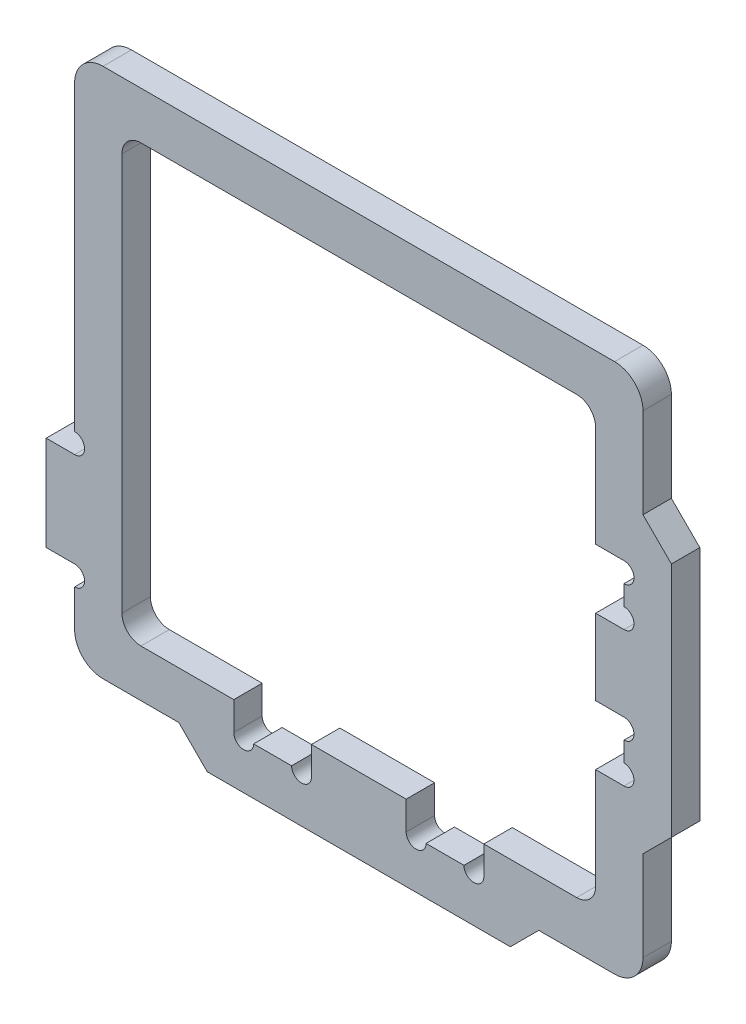
SolidWorks part; units mm, degrees
material "玻纤板"
ref_plane "前视基准面" through (0, 0, 0) normal (0, 0, 1) x (1, 0, 0)
ref_plane "上视基准面" through (0, 0, 0) normal (0, 1, 0) x (1, 0, 0)
ref_plane "右视基准面" through (0, 0, 0) normal (1, 0, 0) x (0, 0, -1)
sketch "草图1" plane through (0, 0, 0) normal (0, 0, 1) x (1, 0, 0)
  line L1 (25, -23) -> (13.2, -23)
  line L2 (25, -23) -> (25, -10.3)
  line L3 (25, 23) -> (-25, 23)
  line L4 (-25, -23) -> (-25, 23)
  line L5 (25, -23) -> (-25, 23) construction
  line L6 (25, 23) -> (-25, -23) construction
  line L11 (-30, -28) -> (-19, -28)
  line L12 (30, -28) -> (30, -23)
  line L14 (-5, -23) -> (-5, -26)
  line L15 (-5, -26) -> (-13.2, -26)
  line L16 (-13.2, -26) -> (-13.2, -23)
  line L17 (5, -23) -> (5, -26)
  line L18 (5, -26) -> (13.2, -26)
  line L19 (13.2, -26) -> (13.2, -23)
  line L20 (0, 0) -> (0, -11.4051) construction
  line L21 (-19, -28) -> (-16, -31)
  line L22 (-16, -31) -> (16, -31)
  line L23 (16, -31) -> (19, -28)
  line L24 (19, -28) -> (30, -28)
  line L25 (-13.2, -23) -> (-25, -23)
  line L26 (5, -23) -> (-5, -23)
  line L27 (25, 10.3) -> (28, 10.3)
  line L28 (28, 10.3) -> (28, 4)
  line L29 (28, 4) -> (25, 4)
  line L30 (25, -4) -> (28, -4)
  line L31 (28, -4) -> (28, -10.3)
  line L32 (28, -10.3) -> (25, -10.3)
  line L33 (0, 0) -> (14.9277, 0) construction
  line L34 (30, 15.5) -> (33, 12.5)
  line L35 (33, 12.5) -> (33, -12.5)
  line L36 (33, -12.5) -> (30, -15.5)
  line L37 (30, 15.5) -> (30, 28)
  line L38 (25, 10.3) -> (25, 23)
  line L39 (25, -4) -> (25, 4)
  line L43 (30, 28) -> (-30, 28)
  line L47 (-30, -19) -> (-30, -23)
  line L48 (30, -18) -> (42, -18) construction
  line L49 (42, -18) -> (39.1132, -23) construction
  line L50 (39.1132, -23) -> (30, -23) construction
  line L51 (30, -18) -> (30, -15.5)
  line L52 (-33, -14) -> (-30, -14) construction
  line L53 (-30, -9) -> (-33, -9)
  line L54 (-33, -9) -> (-33, -19)
  line L55 (-33, -19) -> (-30, -19)
  line L56 (-30, 28) -> (-30, -9)
  line L58 (-30, -28) -> (-30, -23)
  line L60 (-25, 11.2) -> (-28, 11.2) construction
  line L61 (-28, 11.2) -> (-28, 5) construction
  line L62 (-28, 5) -> (-25, 5) construction
  line L63 (-25, -5) -> (-28, -5) construction
  line L64 (-28, -5) -> (-28, -11.2) construction
  line L65 (-28, -11.2) -> (-25, -11.2) construction
  line L70 (30, -23) -> (30, -18)
  circle A2 centre (-6.05, -26) radius 1.05
  circle A3 centre (6.05, -26) radius 1.05
  circle A4 centre (-12.15, -26) radius 1.05
  circle A5 centre (12.15, -26) radius 1.05
  circle A6 centre (28, 9.25) radius 1.05
  circle A7 centre (28, 5.05) radius 1.05
  circle A8 centre (28, -5.05) radius 1.05
  circle A9 centre (28, -9.25) radius 1.05
  circle A14 centre (-30, -7.95) radius 1.05
  circle A15 centre (-30, -20.05) radius 1.05
  circle A16 centre (-28, -6.05) radius 1.05 construction
  circle A17 centre (-28, 6.05) radius 1.05 construction
  point P0 (0, 0)
  point P53 (28, 7.15)
  point P67 (-30, -6.9)
  point P68 (-30, -7.95)
  point P74 (-29.3542, -20.0366)
  dimension "D10" = 25
  dimension "D16" = 2.1
  dimension "D20" = 2.1
  dimension "D1" = 46
  dimension "D2" = 50
  dimension "D3" = 5
  dimension "D4" = 5
  dimension "D5" = 5
  dimension "D6" = 5
  dimension "D7" = 8
  dimension "D8" = 6.3
  dimension "D9" = 3
  dimension "D11" = 45
  dimension "D12" = 5
  dimension "D13" = 3
  dimension "D14" = 8.2
  dimension "D15" = 10
  dimension "D17" = 32
  dimension "D18" = 45
  dimension "D19" = 5
  dimension "D21" = 14
  dimension "D22" = 18
  dimension "D23" = 12
  dimension "D24" = 60
  dimension "D25" = 3
  dimension "D26" = 10
  dimension "D29" = 9
  dimension "D30" = 10
  dimension "D31" = 6.2
  dimension "D32" = 5
extrude "凸台-拉伸1" add sketch "草图1" along normal blind 3
fillet "圆角1" radius 3 4 edges at (-30, -28, 1.5) (30, -28, 1.5) (30, 28, 1.5) (-30, 28, 1.5)
fillet "圆角2" radius 2 4 edges at (25, 23, 1.5) (25, -23, 1.5) (-25, -23, 1.5) (-25, 23, 1.5)
